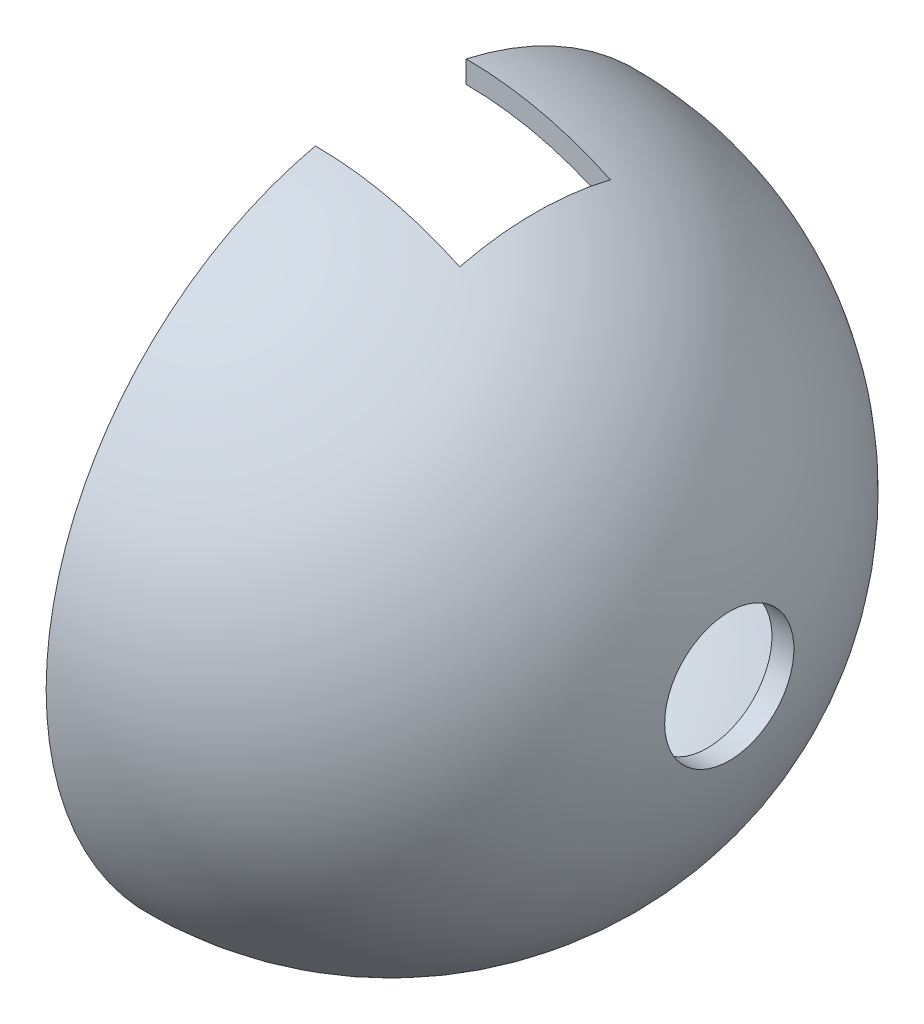
SolidWorks part; units mm, degrees
ref_plane "前视基准面" through (0, 0, 0) normal (0, 0, 1) x (1, 0, 0)
ref_plane "上视基准面" through (0, 0, 0) normal (0, 1, 0) x (1, 0, 0)
ref_plane "右视基准面" through (0, 0, 0) normal (1, 0, 0) x (0, 0, -1)
sketch "草图1" plane through (0, 0, 0) normal (1, 0, 0) x (0, 0, -1)
  line L0 (-16, 0) -> (-15, 0)
  line L1 (15, 0) -> (16, 0)
  arc A0 (15, 0) -> (-15, 0) centre (0, 0) ccw
  arc A1 (16, 0) -> (-16, 0) centre (0, 0) ccw
  point P6 (0, 0)
  point P7 (15, 0)
  point P8 (-15, 0)
  dimension "D1" = 30
  dimension "D2" = 32
ref_plane "基准面4" through (0, 27.8145, 0) normal (0, 1, 0) x (1, 0, 0)
revolve "旋转2" add sketch "草图1" angle 180 about L1
ref_plane "基准面5" through (20.2959, 0, 0) normal (1, 0, 0) x (0, 0, -1)
sketch "草图3" plane through (20.2959, 0, 0) normal (1, 0, 0) x (0, 0, -1)
  circle A0 centre (0, 0) radius 3
  dimension "D1" = 6
extrude "切除-拉伸1" cut sketch "草图3" against normal blind 10
sketch "草图4" plane through (0, 27.8145, 0) normal (0, 1, 0) x (1, 0, 0)
  line L0 (0, 15) -> (0, -15) construction
  line L1 (0, 3.5) -> (6.7, 3.5)
  line L2 (0, 3.5) -> (0, -3.5)
  line L3 (0, -3.5) -> (6.7, -3.5)
  line L4 (6.7, 3.5) -> (6.7, -3.5)
  dimension "D1" = 7
  dimension "D2" = 6.7
extrude "切除-拉伸2" cut sketch "草图4" against normal blind 20
